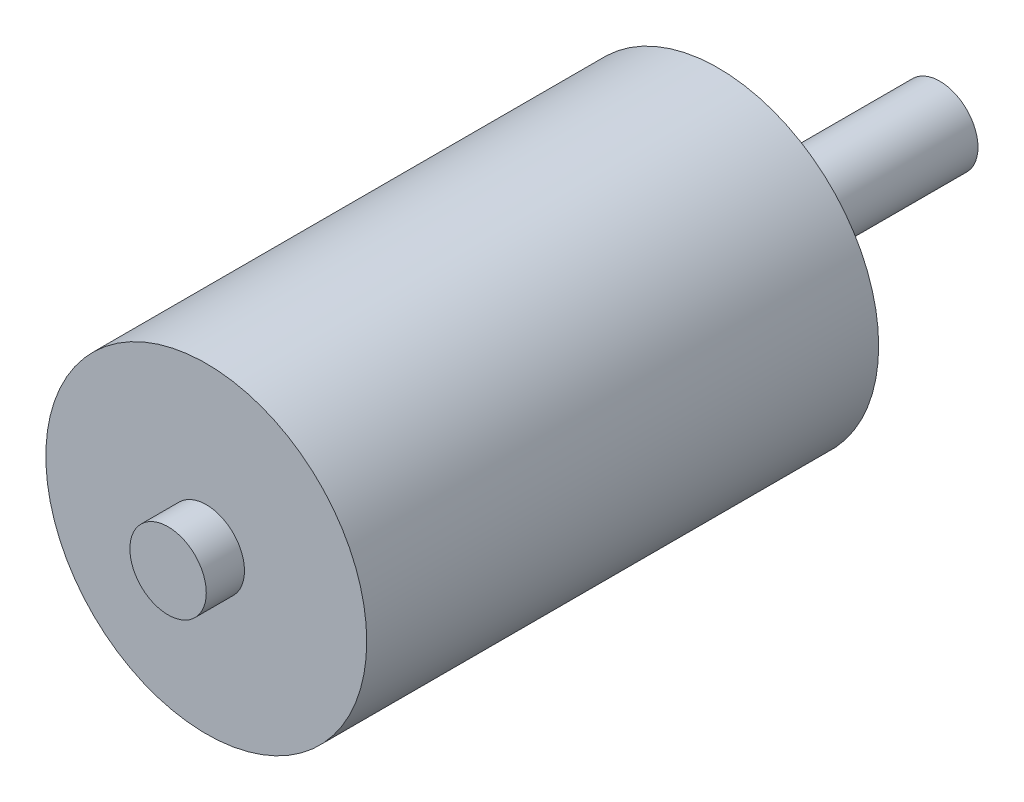
SolidWorks part; units mm, degrees
ref_plane "前视基准面" through (0, 0, 0) normal (0, 0, 1) x (1, 0, 0)
ref_plane "上视基准面" through (0, 0, 0) normal (0, 1, 0) x (1, 0, 0)
ref_plane "右视基准面" through (0, 0, 0) normal (1, 0, 0) x (0, 0, -1)
sketch "草图1" plane through (0, 0, 0) normal (0, 0, 1) x (1, 0, 0)
  circle A0 centre (0, 0) radius 21
extrude "凸台-拉伸1" add sketch "草图1" along normal blind 67
sketch "草图3" plane through (0, 0, 0) normal (0, 0, 1) x (1, 0, 0)
  circle A0 centre (0, 0) radius 13
extrude "凸台-拉伸3" add sketch "草图3" against normal blind 2
sketch "草图4" plane through (0, 0, 0) normal (0, 0, 1) x (1, 0, 0)
  circle A0 centre (0, 0) radius 5
extrude "凸台-拉伸4" add sketch "草图4" against normal blind 29
sketch "草图5" plane through (0, 0, 0) normal (0, 0, 1) x (1, 0, 0)
  circle A0 centre (0, 0) radius 17.5 construction
  circle A1 centre (17.5, 0) radius 2.016
  circle A2 centre (0, -17.5) radius 2.0402
  circle A3 centre (-17.5, 0) radius 1.9371
  circle A4 centre (0, 17.5) radius 2
  circle A5 centre (12.5572, 12.1888) radius 2
  circle A6 centre (-12.5572, 12.1888) radius 2
  circle A7 centre (-12.5572, -12.1888) radius 2
  circle A8 centre (12.5572, -12.1888) radius 2
  circle A9 centre (0, 0) radius 4.5
extrude "凸台-拉伸5" add sketch "草图5" along normal blind 0.7
sketch "草图6" plane through (0, 0, 0) normal (0, 0, 1) x (1, 0, 0)
  circle A0 centre (0, 0) radius 17.5 construction
  circle A1 centre (-17.5, 0) radius 2
  circle A2 centre (17.5, 0) radius 2
  circle A3 centre (0, 17.5) radius 2
  circle A4 centre (0, -17.5) radius 2
sketch "草图7" plane through (0, 0, 67) normal (0, 0, 1) x (1, 0, 0)
  circle A0 centre (0, 0) radius 5
extrude "凸台-拉伸6" add sketch "草图7" along normal blind 5
extrude "切除-拉伸1" cut sketch "草图6" along normal blind 7
